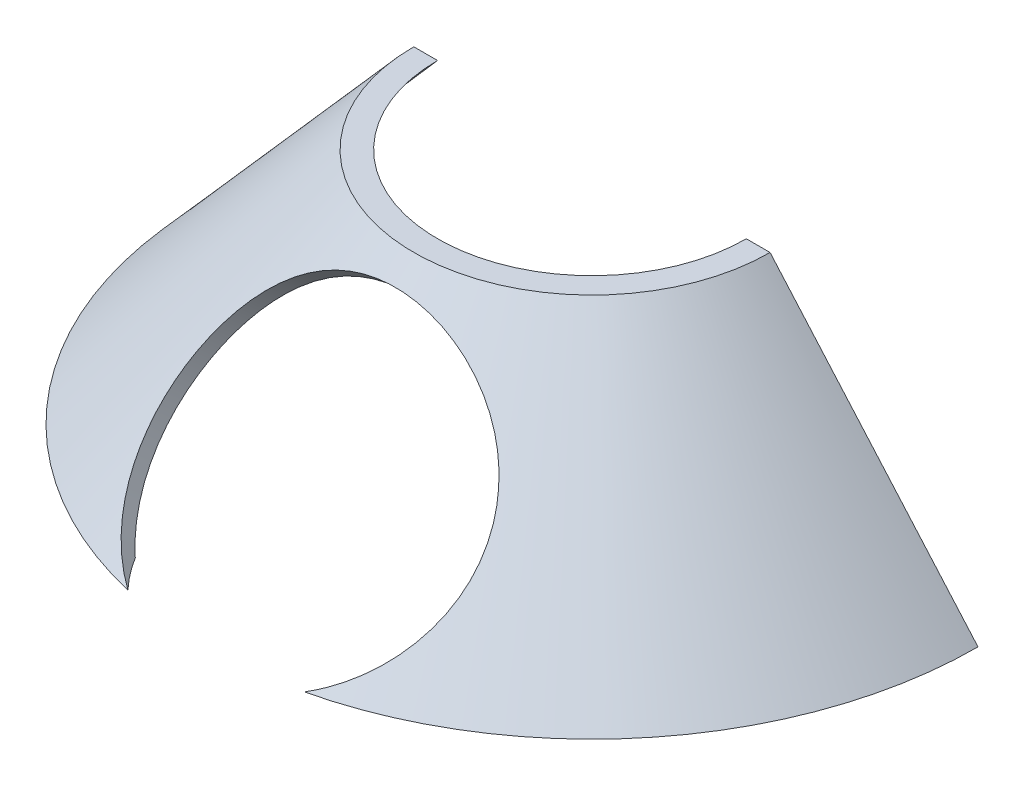
SolidWorks part; units mm, degrees
ref_plane "Front Plane" through (0, 0, 0) normal (0, 0, 1) x (1, 0, 0)
ref_plane "Top Plane" through (0, 0, 0) normal (0, 1, 0) x (1, 0, 0)
ref_plane "Right Plane" through (0, 0, 0) normal (1, 0, 0) x (0, 0, -1)
sketch "Sketch1" plane through (0, 0, 0) normal (0, 0, 1) x (1, 0, 0)
  line L0 (0, 40) -> (0, 0) construction
  line L1 (0, -55) -> (0, 55) construction
  line L2 (26, 40) -> (61, 0)
  line L3 (55, 0) -> (-55, 0) construction
  line L4 (26, 40) -> (30, 40)
  line L5 (30, 40) -> (65.0138, -0.0158)
  line L6 (65.0138, -0.0158) -> (61, 0)
  point P9 (86.101, 0)
  dimension "D1" = 40
  dimension "D2" = 26
  dimension "D3" = 61
  dimension "D4" = 4
revolve "Revolve1" add sketch "Sketch1" angle 180 about L0
ref_plane "Plane1" through (0, 32.2124, 36.8142) normal (0, 0.6585, 0.7526) x (1, 0, 0)
sketch "Sketch3" plane through (0, 32.2124, 36.8142) normal (0, 0.6585, 0.7526) x (1, 0, 0)
  circle A0 centre (0, -20.3521) radius 26
  point P2 (0, 0)
  point P3 (0, -20.3521)
  dimension "D1" = 52
extrude "Cut-Extrude1" cut sketch "Sketch3" against normal blind 10
